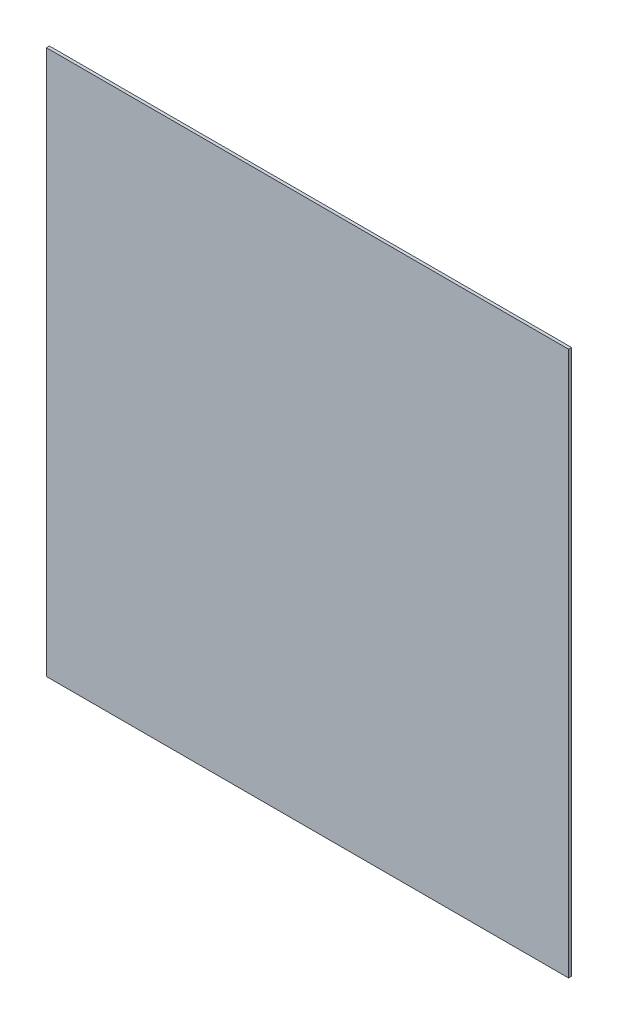
SolidWorks part; units mm, degrees
material "ABS"
ref_plane "Front Plane" through (0, 0, 0) normal (0, 0, 1) x (1, 0, 0)
ref_plane "Top Plane" through (0, 0, 0) normal (0, 1, 0) x (1, 0, 0)
ref_plane "Right Plane" through (0, 0, 0) normal (1, 0, 0) x (0, 0, -1)
sketch "Sketch1" plane through (0, 0, 0) normal (0, 0, 1) x (1, 0, 0)
  line L1 (-436.25, -455) -> (436.25, -455)
  line L2 (-436.25, -455) -> (-436.25, 455)
  line L3 (-436.25, 455) -> (436.25, 455)
  line L4 (436.25, -455) -> (436.25, 455)
  line L5 (-436.25, -455) -> (436.25, 455) construction
  line L6 (-436.25, 455) -> (436.25, -455) construction
  point P0 (0, 0)
  dimension "D1" = 872.5
  dimension "D2" = 910
extrude "Boss-Extrude1" add sketch "Sketch1" along normal blind 5
